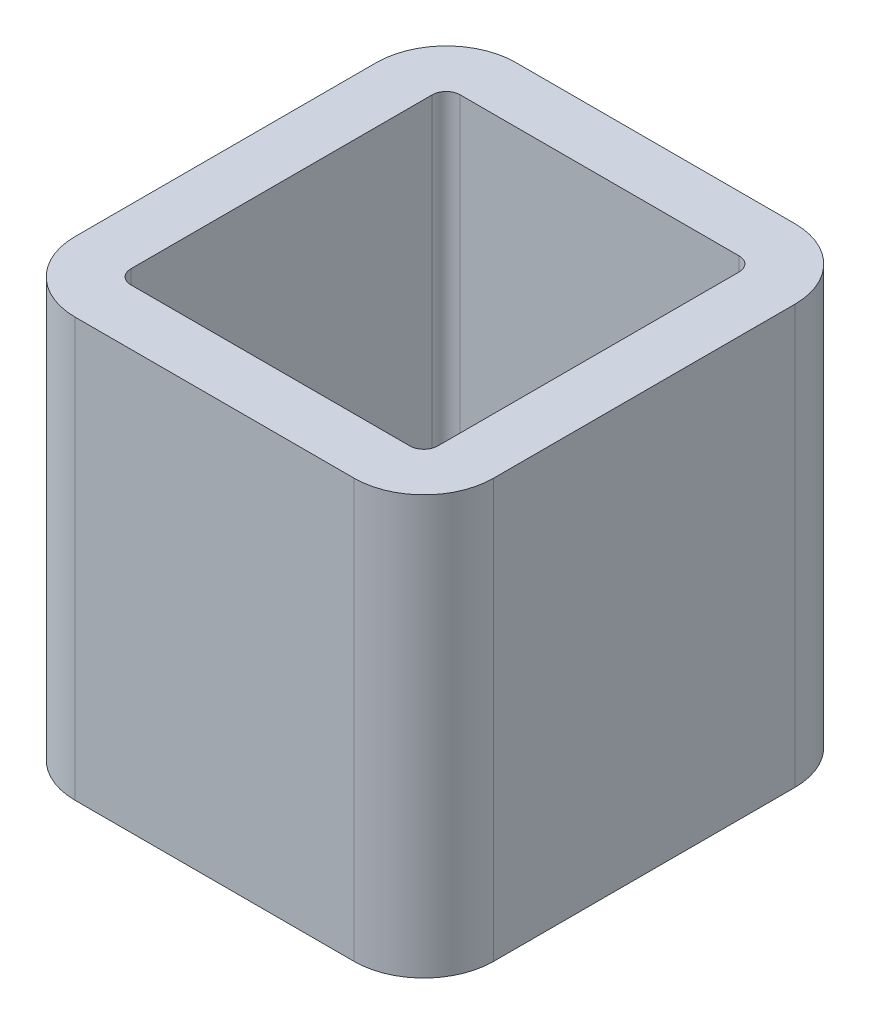
SolidWorks part; units mm, degrees
ref_plane "Front Plane" through (0, 0, 0) normal (0, 0, 1) x (1, 0, 0)
ref_plane "Top Plane" through (0, 0, 0) normal (0, 1, 0) x (1, 0, 0)
ref_plane "Right Plane" through (0, 0, 0) normal (1, 0, 0) x (0, 0, -1)
sketch "Sketch1" plane through (0, 0, 0) normal (0, 1, 0) x (1, 0, 0)
  line L1 (-150, 158) -> (150, 158)
  line L2 (-150, 158) -> (-150, -158)
  line L3 (-150, -158) -> (150, -158)
  line L4 (150, 158) -> (150, -158)
  point P4 (-150, 0)
  point P5 (0, -158)
  dimension "D1" = 316
  dimension "D2" = 300
extrude "Boss-Extrude1" add sketch "Sketch1" along normal blind 300
fillet "Fillet1" radius 50 4 edges at (-150, 150, -158) (150, 150, -158) (-150, 150, 158) (150, 150, 158)
shell "Shell1" thickness 40
